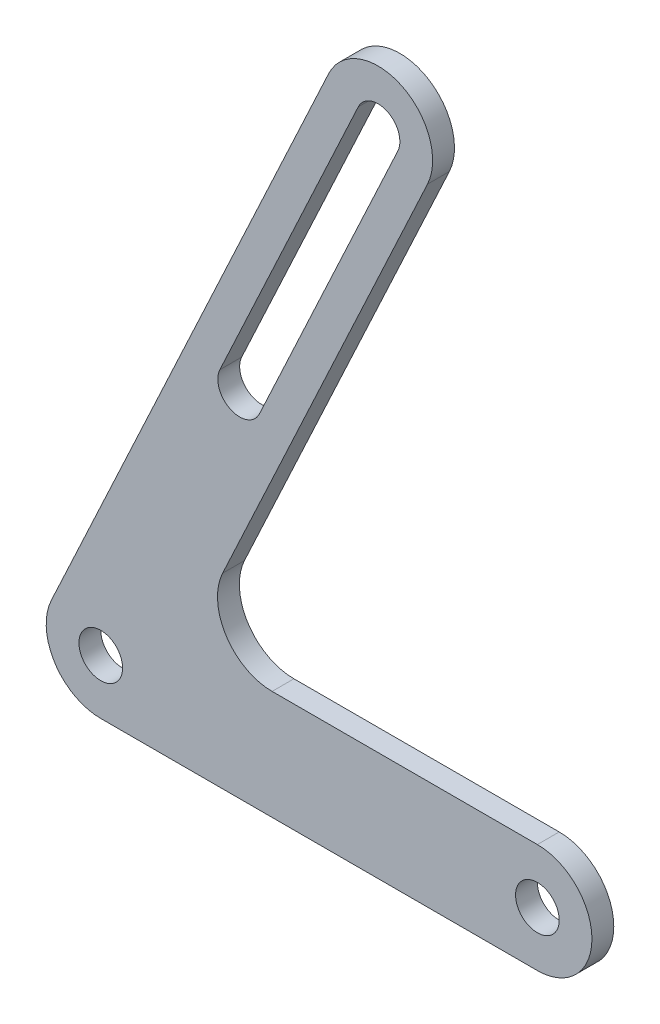
SolidWorks part; units mm, degrees
ref_plane "Front Plane" through (0, 0, 0) normal (0, 0, 1) x (1, 0, 0)
ref_plane "Top Plane" through (0, 0, 0) normal (0, 1, 0) x (1, 0, 0)
ref_plane "Right Plane" through (0, 0, 0) normal (1, 0, 0) x (0, 0, -1)
sketch "Sketch1" plane through (0, 0, 0) normal (0, 0, 1) x (1, 0, 0)
  line L0 (0, 0) -> (80, 0) construction
  line L1 (80, 0) -> (50.8059, 108.9537) construction
  line L2 (50.8059, 108.9537) -> (0, 0) construction
  line L3 (0, 0) -> (50.8059, 108.9537) construction
  line L4 (-9.0631, 4.2262) -> (41.7429, 113.1799)
  line L5 (9.0631, -4.2262) -> (59.869, 104.7275)
  line L6 (0, 0) -> (80, 0) construction
  line L7 (0, 10) -> (80, 10)
  line L8 (0, -10) -> (80, -10)
  arc A0 (-9.0631, 4.2262) -> (9.0631, -4.2262) centre (0, 0) ccw
  arc A1 (59.869, 104.7275) -> (41.7429, 113.1799) centre (50.8059, 108.9537) ccw
  arc A2 (0, 10) -> (0, -10) centre (0, 0) ccw
  arc A3 (80, -10) -> (80, 10) centre (80, 0) ccw
  point P3 (25.403, 54.4768)
  point P9 (40, 0)
  dimension "D4" = 10
  dimension "D5" = 10
  dimension "D1" = 80
  dimension "D2" = 75
  dimension "D3" = 65
extrude "Boss-Extrude1" add sketch "Sketch1" along normal mid plane 4 contours A2 L7 L5 A1 L4 | L7 A2 A0 L5 | L8 A3 L7 L5 A0
sketch "Sketch2" plane through (0, 0, 0) normal (0, 0, 1) x (1, 0, 0)
  line L0 (50.8059, 108.9537) -> (25.4488, 54.5752) construction
  line L1 (54.4312, 107.2632) -> (29.0741, 52.8848)
  line L2 (47.1807, 110.6442) -> (21.8236, 56.2657)
  line L4 (41.7429, 113.1799) -> (-9.0631, 4.2262)
  line L5 (0, -10) -> (80, -10)
  line L6 (80, 10) -> (15.6969, 10)
  line L7 (15.6969, 10) -> (59.869, 104.7275)
  line L8 (41.7429, 113.1799) -> (-9.0631, 4.2262)
  line L9 (0, -10) -> (80, -10)
  line L10 (80, 10) -> (15.6969, 10)
  line L11 (15.6969, 10) -> (59.869, 104.7275)
  arc A0 (54.4312, 107.2632) -> (47.1807, 110.6442) centre (50.8059, 108.9537) ccw
  arc A1 (21.8236, 56.2657) -> (29.0741, 52.8848) centre (25.4488, 54.5752) ccw
  circle A2 centre (0, 0) radius 4
  arc A3 (-9.0631, 4.2262) -> (0, -10) centre (0, 0) ccw
  arc A4 (80, -10) -> (80, 10) centre (80, 0) ccw
  arc A5 (59.869, 104.7275) -> (41.7429, 113.1799) centre (50.8059, 108.9537) ccw
  arc A6 (-9.0631, 4.2262) -> (0, -10) centre (0, 0) ccw
  arc A7 (80, -10) -> (80, 10) centre (80, 0) ccw
  arc A8 (59.869, 104.7275) -> (41.7429, 113.1799) centre (50.8059, 108.9537) ccw
  circle A9 centre (80, 0) radius 4
  point P7 (38.1274, 81.7645)
  dimension "D2" = 4
  dimension "D3" = 60
  dimension "D4" = 8
  dimension "D1" = 0
extrude "Cut-Extrude1" cut sketch "Sketch2" against normal through all and the other way blind 4 contours A9 | L2 A1 L1 A0 | A2
fillet "Fillet1" radius 10 1 edges at (15.6969, 10, 0)
